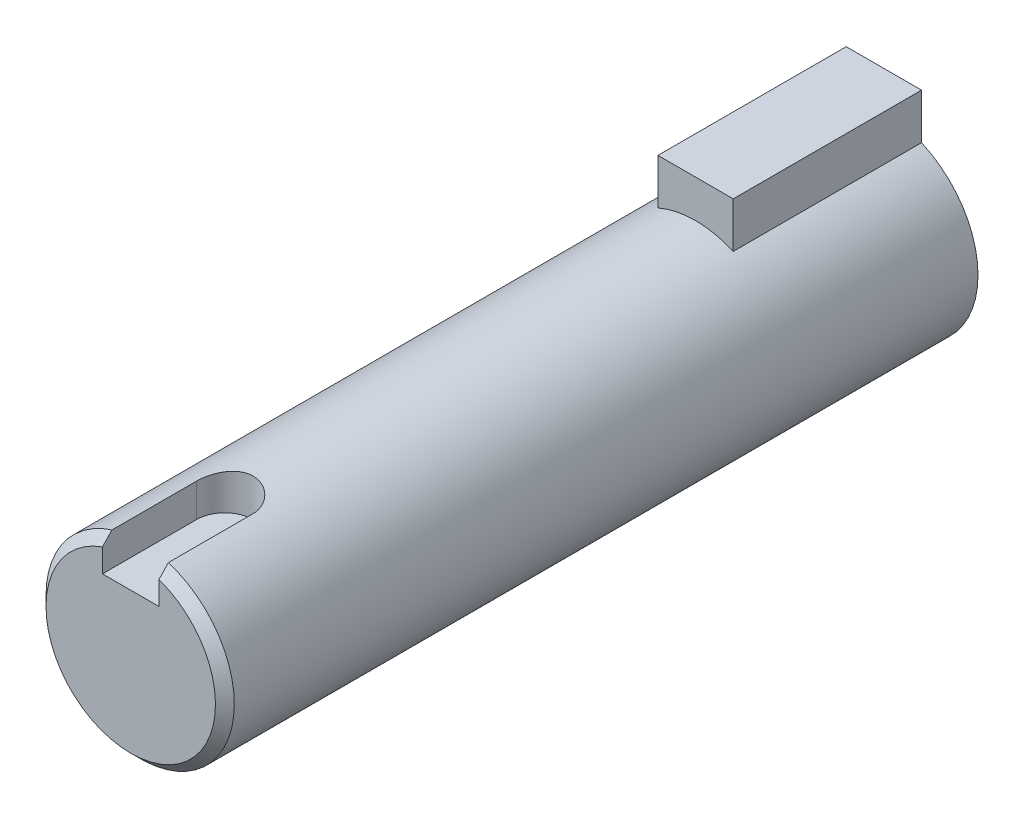
SolidWorks part; units mm, degrees
ref_plane "Front Plane" through (0, 0, 0) normal (0, 0, 1) x (1, 0, 0)
ref_plane "Top Plane" through (0, 0, 0) normal (0, 1, 0) x (1, 0, 0)
ref_plane "Right Plane" through (0, 0, 0) normal (1, 0, 0) x (0, 0, -1)
sketch "Sketch1" plane through (0, 0, 0) normal (0, 0, 1) x (1, 0, 0)
  line L1 (-2, 7) -> (2, 7)
  line L2 (-2, 7) -> (-2, 4.5826)
  line L4 (2, 7) -> (2, 4.5826)
  arc A0 (-2, 4.5826) -> (2, 4.5826) centre (0, 0) ccw
  point P3 (0, 5)
  dimension "D1" = 10
  dimension "D2" = 4
  dimension "D3" = 7
  dimension "D4" = 2.4174
extrude "Boss-Extrude1" add sketch "Sketch1" along normal blind 10
sketch "Sketch2" plane through (0, 0, 10) normal (0, 0, 1) x (1, 0, 0)
  circle A0 centre (0, 0) radius 5
extrude "Boss-Extrude2" add sketch "Sketch2" along normal blind 30
sketch "Sketch3" plane through (0, 0, 0) normal (0, 1, 0) x (1, 0, 0)
  line L0 (0, -40) -> (0, -35) construction
  line L1 (-5, -40) -> (5, -40) construction
  line L2 (-1.5, -40) -> (-1.5, -35)
  line L3 (1.5, -40) -> (1.5, -35)
  arc A0 (-1.5, -40) -> (1.5, -40) centre (0, -40) ccw
  arc A1 (1.5, -35) -> (-1.5, -35) centre (0, -35) ccw
  point P5 (0, -37.5)
  dimension "D1" = 3
  dimension "D2" = 5
extrude "Cut-Extrude1" cut sketch "Sketch3" along normal through all from offset 3
chamfer "Chamfer1" distance 0.5 angle 45 1 edges at (0, -5, 40)
